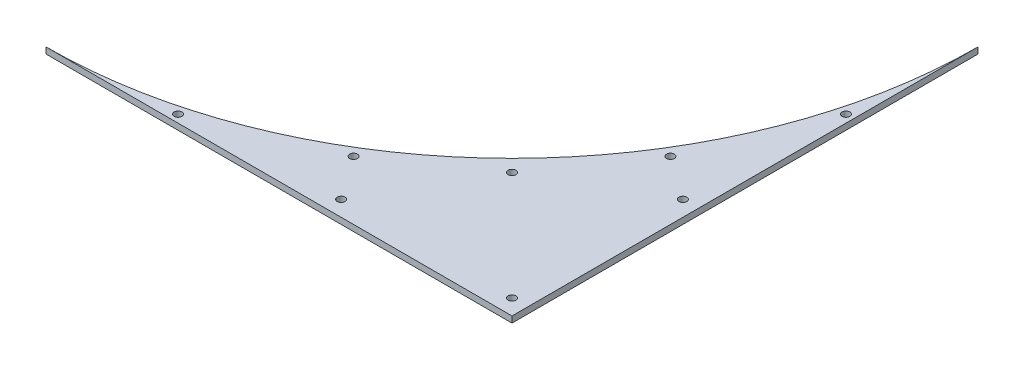
SolidWorks part; units mm, degrees
ref_plane "Front Plane" through (0, 0, 0) normal (0, 0, 1) x (1, 0, 0)
ref_plane "Top Plane" through (0, 0, 0) normal (0, 1, 0) x (1, 0, 0)
ref_plane "Right Plane" through (0, 0, 0) normal (1, 0, 0) x (0, 0, -1)
sketch "Sketch1" plane through (0, 0, 0) normal (0, 1, 0) x (1, 0, 0)
  line L1 (0, 0) -> (381, 0)
  line L2 (0, 0) -> (0, 381)
  line L3 (0, 381) -> (381, 381)
  line L4 (381, 0) -> (381, 381)
  line L5 (0, 381) -> (-203.2, 381)
  line L6 (0, 381) -> (0, 0)
  line L7 (0, 0) -> (-203.2, 0)
  line L8 (-203.2, 381) -> (-203.2, 0)
  arc A0 (381, 381) -> (0, 0) centre (0, 381) cw
  circle A1 centre (39.2386, 142.9117) radius 139.7
  circle A2 centre (0, 381) radius 101.6
  circle A3 centre (196.7476, 241.3) radius 139.7
  circle A4 centre (86.3584, 155.6826) radius 139.7
  circle A5 centre (-59.7956, 143.4044) radius 143.4044
  dimension "D1" = 381
  dimension "D2" = 381
  dimension "D3" = 203.2
sketch "Sketch2" plane through (0, 0, 0) normal (0, 1, 0) x (1, 0, 0)
  line L0 (-203.2, 381) -> (-44.423, 381)
  line L1 (44.0206, 381) -> (381, 381)
  line L2 (-203.2, 381) -> (-203.2, 0)
  line L3 (-203.2, 0) -> (381, 0)
  line L4 (381, 381) -> (381, 0)
  line L6 (-44.423, 381) -> (-44.423, 423.7475)
  line L7 (-44.423, 423.7475) -> (44.0206, 423.7475)
  line L8 (44.0206, 381) -> (44.0206, 423.7475)
extrude "Boss-Extrude1" add sketch "Sketch1" along normal blind 5.08 contours L4 A0 L1
sketch "Sketch3" plane through (0, 5.08, 0) normal (0, 1, 0) x (1, 0, 0)
  line L0 (381, 0) -> (381, 381) construction
  line L1 (0, 0) -> (381, 0) construction
  circle A0 centre (101.6, 6.35) radius 3.175
  circle A1 centre (374.65, 279.4) radius 3.175
  circle A2 centre (368.3, 12.7) radius 3.175
  circle A3 centre (279.4, 101.6) radius 3.175
  circle A4 centre (203.2, 48.26) radius 3.175
  circle A5 centre (332.74, 177.8) radius 3.175
  circle A7 centre (228.6, 12.7) radius 3.175
  circle A8 centre (368.3, 152.4) radius 3.175
  dimension "D1" = 279.4
  dimension "D13" = 12.7
  dimension "D2" = 6.35
  dimension "D3" = 177.8
  dimension "D4" = 48.26
  dimension "D5" = 101.6
  dimension "D6" = 101.6
  dimension "D7" = 48.26
  dimension "D8" = 177.8
  dimension "D9" = 6.35
  dimension "D10" = 279.4
  dimension "D11" = 12.7
  dimension "D12" = 12.7
  dimension "D14" = 152.4
  dimension "D15" = 12.7
  dimension "D16" = 152.4
extrude "Cut-Extrude1" cut sketch "Sketch3" against normal blind 5.08
